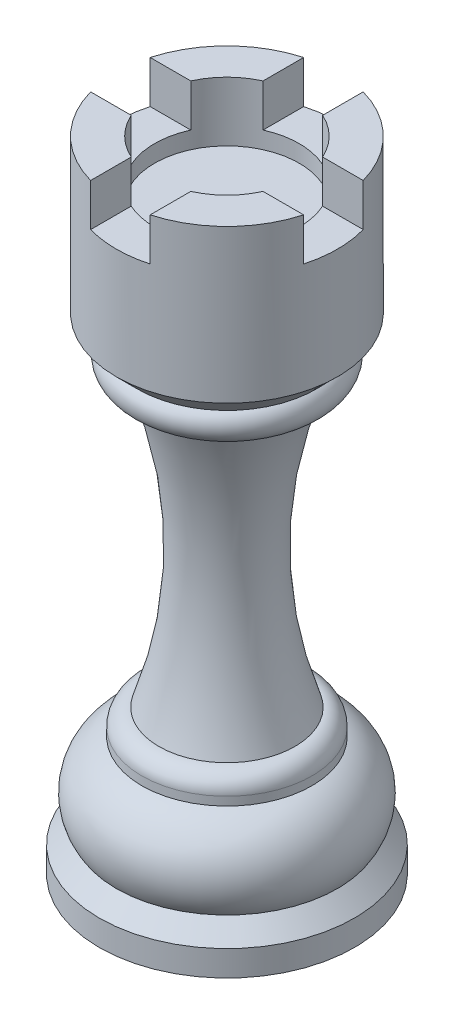
SolidWorks part; units mm, degrees
ref_plane "Front Plane" through (0, 0, 0) normal (0, 0, 1) x (1, 0, 0)
ref_plane "Top Plane" through (0, 0, 0) normal (0, 1, 0) x (1, 0, 0)
ref_plane "Right Plane" through (0, 0, 0) normal (1, 0, 0) x (0, 0, -1)
sketch "Sketch1" plane through (0, 0, 0) normal (0, 0, 1) x (1, 0, 0)
  line L0 (0, 0) -> (0, 72.2592) construction
  line L1 (0, 0) -> (-15, 0)
  line L2 (-15, 0) -> (-15, 3)
  line L3 (-15, 3) -> (-13, 5)
  line L4 (-10, 13.97) -> (-10, 14.97)
  line L5 (-10.5, 54.594) -> (-13, 57.094)
  line L6 (-13, 57.094) -> (-13, 75.094)
  line L7 (-13, 75.094) -> (-8.5, 75.094)
  line L8 (0, 75.094) -> (0, 0) construction
  line L9 (-8.5, 75.094) -> (-8.5, 68.094)
  line L10 (-8.5, 68.094) -> (0, 68.094)
  line L11 (0, 68.094) -> (0, 0)
  arc A0 (-13, 5) -> (-10, 13.97) centre (-7.9981, 8.3138) cw
  arc A1 (-10, 14.97) -> (-8, 16.97) centre (-8, 14.97) cw
  arc A2 (-8, 16.97) -> (-8.5, 51.17) centre (-55.2293, 33.3832) ccw
  arc A3 (-8.5, 51.17) -> (-10.5, 54.594) centre (-9.273, 53.0146) cw
  point P15 (-11, 52.0058)
  dimension "D6" = 6
  dimension "D9" = 2
  dimension "D12" = 50
  dimension "D15" = 2
  dimension "D1" = 30
  dimension "D2" = 3
  dimension "D3" = 2
  dimension "D4" = 26
  dimension "D5" = 8.97
  dimension "D7" = 20
  dimension "D8" = 1
  dimension "D10" = 16
  dimension "D11" = 17
  dimension "D13" = 34.2
  dimension "D14" = 22
  dimension "D16" = 21
  dimension "D17" = 2.5
  dimension "D18" = 45
  dimension "D19" = 18
  dimension "D20" = 17
  dimension "D21" = 7
revolve "Revolve2" add sketch "Sketch1" angle 360 about L8
sketch "Sketch2" plane through (0, 75.094, 0) normal (0, 1, 0) x (1, 0, 0)
  line L0 (0, 0) -> (21.4329, 0) construction
  line L1 (7.746, -3.5) -> (12.52, -3.5)
  line L2 (7.746, 3.5) -> (12.52, 3.5)
  line L4 (0, -3.5) -> (21.4329, -3.5) construction
  line L5 (0, 3.5) -> (21.4329, 3.5) construction
  circle A0 centre (0, 0) radius 13 construction
  circle A1 centre (0, 0) radius 13
  circle A2 centre (0, 0) radius 8.5 construction
  circle A3 centre (0, 0) radius 8.5
  circle M2 centre (0, 0) radius 13
  circle M3 centre (0, 0) radius 8.5
  dimension "D1" = 3.5
  dimension "D2" = 3.5
extrude "Cut-Extrude1" cut sketch "Sketch2" against normal blind 5 contours L2 L1 M3 M2
pattern_circular "CirPattern1" count 4 over 360 about axis through (0, 0, 0) along (0, 1, 0) of "Cut-Extrude1"
